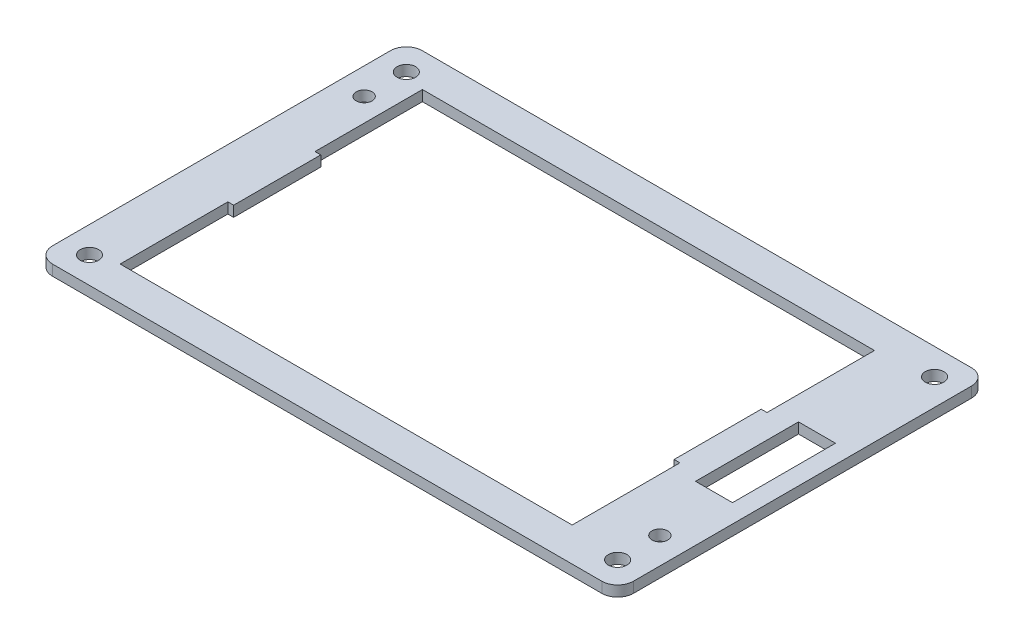
SolidWorks part; units mm, degrees
ref_plane "Front Plane" through (0, 0, 0) normal (0, 0, 1) x (1, 0, 0)
ref_plane "Top Plane" through (0, 0, 0) normal (0, 1, 0) x (1, 0, 0)
ref_plane "Right Plane" through (0, 0, 0) normal (1, 0, 0) x (0, 0, -1)
sketch "Sketch1" plane through (0, 0, 0) normal (0, 1, 0) x (1, 0, 0)
  line L0 (0, 30) -> (0, 0) construction
  line L1 (-50, 30) -> (50, 30) construction
  line L2 (-50, 30) -> (-50, -30) construction
  line L3 (-50, -30) -> (50, -30) construction
  line L4 (50, 30) -> (50, -30) construction
  line L5 (0, 0) -> (0, -30) construction
  line L6 (39.9848, 28.6429) -> (-45.603, 28.6429)
  line L7 (-55, 35) -> (55, 35)
  line L8 (-55, 35) -> (-55, -35)
  line L9 (-55, -35) -> (55, -35)
  line L10 (55, 35) -> (55, -35)
  line L11 (-45.603, 28.6429) -> (-45.603, 8.2998)
  line L12 (-45.603, 8.2998) -> (-44.51, 8.2998)
  line L13 (-44.51, 8.2998) -> (-44.51, -8.2002)
  line L14 (-44.51, -8.2002) -> (-45.603, -8.2002)
  line L15 (-45.603, -8.2002) -> (-45.603, -28.5913)
  line L16 (-45.603, -28.5913) -> (39.9848, -28.5913)
  line L17 (39.9848, -28.5913) -> (39.9848, -8.2002)
  line L18 (39.9848, -8.2002) -> (38.89, -8.2002)
  line L19 (-55, 0) -> (0, 0) construction
  line L20 (38.89, -8.2002) -> (38.89, 8.2998)
  line L21 (38.89, 8.2998) -> (39.9848, 8.2998)
  line L22 (39.9848, 8.2998) -> (39.9848, 28.6429)
  line L24 (0, 0) -> (55, 0) construction
  line L25 (-44.31, 15.3) -> (-44.31, -22.2) construction
  line L26 (-45.3943, 8.4996) -> (-45.3943, 8.2998) construction
  line L27 (-45.403, 12.2551) -> (-45.403, 8.4996) construction
  line L28 (-45.403, -8.2002) -> (-45.403, -8.4) construction
  line L29 (38.69, 27.3) -> (38.69, -27.2) construction
  line L30 (39.7848, 18.7266) -> (39.7848, 22.3585) construction
  line L31 (12.7455, 28.4429) -> (9.8328, 28.4429) construction
  line L33 (-18.903, -28.3913) -> (-15.4118, -28.3913) construction
  circle A0 centre (-50, 30) radius 1.75
  circle A1 centre (-50, -30) radius 1.75
  circle A2 centre (50, -30) radius 1.75
  circle A3 centre (50, 30) radius 1.75
  dimension "D1" = 3.5
  dimension "D2" = 60
  dimension "D3" = 100
  dimension "D4" = 16.5
  dimension "D5" = 0.2
  dimension "D6" = 0.2
  dimension "D7" = 0.2
  dimension "D8" = 0.2
  dimension "D9" = 0.2
  dimension "D10" = 5
  dimension "D11" = 5
  dimension "D12" = 110
  dimension "D13" = 0.2
extrude "Boss-Extrude1" add sketch "Sketch1" along normal blind 2
sketch "Sketch2" plane through (0, 2, 0) normal (0, 1, 0) x (1, 0, 0)
  line L0 (44.5, 0) -> (51.5, 0) construction
  line L1 (44.5, -9.75) -> (51.5, -9.75)
  line L2 (44.5, -9.75) -> (44.5, 9.75)
  line L3 (44.5, 9.75) -> (51.5, 9.75)
  line L5 (51.5, -9.75) -> (51.5, 9.75)
  line L8 (44.675, -8.525) -> (51.325, -8.525) construction
  line L9 (48, -8.525) -> (48, 0) construction
  line L10 (48, 0) -> (48, 8.525) construction
  line L11 (51.325, 8.525) -> (44.675, 8.525) construction
  dimension "D1" = 7
  dimension "D2" = 19.5
extrude "Cut-Extrude1" cut sketch "Sketch2" against normal through all
fillet "Fillet1" radius 3 4 edges at (-55, 1, -35) (-55, 1, 35) (55, 1, -35) (55, 1, 35)
sketch "Sketch3" plane through (0, 0, 0) normal (0, -1, 0) x (1, 0, 0)
  circle A0 centre (50, 22) radius 1.5
  circle A1 centre (-50, -22) radius 1.5
  dimension "D1" = 3
extrude "Cut-Extrude2" cut sketch "Sketch3" against normal through all
